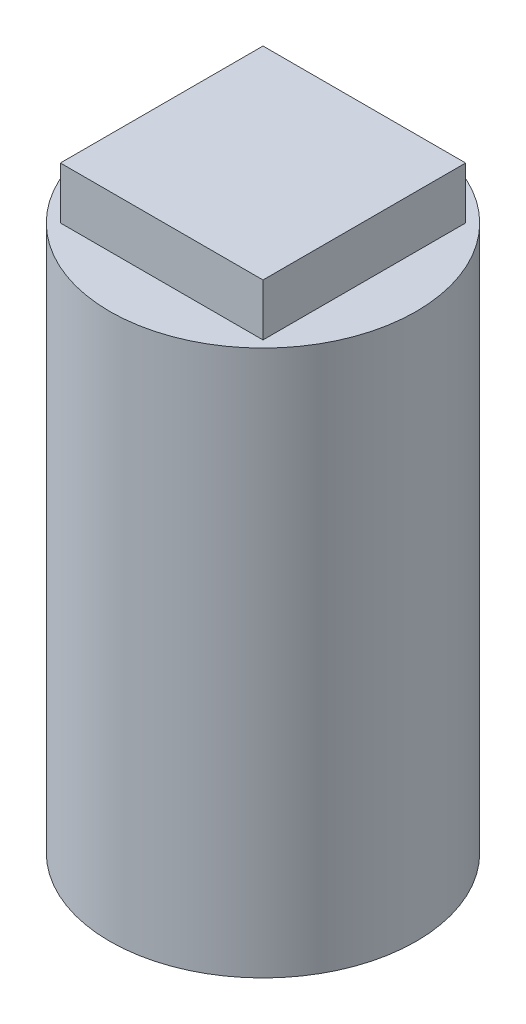
SolidWorks part; units mm, degrees
ref_plane "Front Plane" through (0, 0, 0) normal (0, 0, 1) x (1, 0, 0)
ref_plane "Top Plane" through (0, 0, 0) normal (0, 1, 0) x (1, 0, 0)
ref_plane "Right Plane" through (0, 0, 0) normal (1, 0, 0) x (0, 0, -1)
sketch "Sketch1" plane through (0, 0, 0) normal (0, 1, 0) x (1, 0, 0)
  circle A0 centre (0, 0) radius 2.95
  dimension "D1" = 5.9
extrude "Boss-Extrude1" add sketch "Sketch1" along normal blind 10.5
sketch "Sketch2" plane through (0, 10.5, 0) normal (0, 1, 0) x (1, 0, 0)
  line L1 (1.95, 1.95) -> (-1.95, 1.95)
  line L2 (1.95, 1.95) -> (1.95, -1.95)
  line L3 (1.95, -1.95) -> (-1.95, -1.95)
  line L4 (-1.95, 1.95) -> (-1.95, -1.95)
  line L5 (1.95, 1.95) -> (-1.95, -1.95) construction
  line L6 (1.95, -1.95) -> (-1.95, 1.95) construction
  point P0 (0, 0)
  dimension "D1" = 3.9
  dimension "D2" = 3.9
extrude "Boss-Extrude3" add sketch "Sketch2" along normal blind 1
